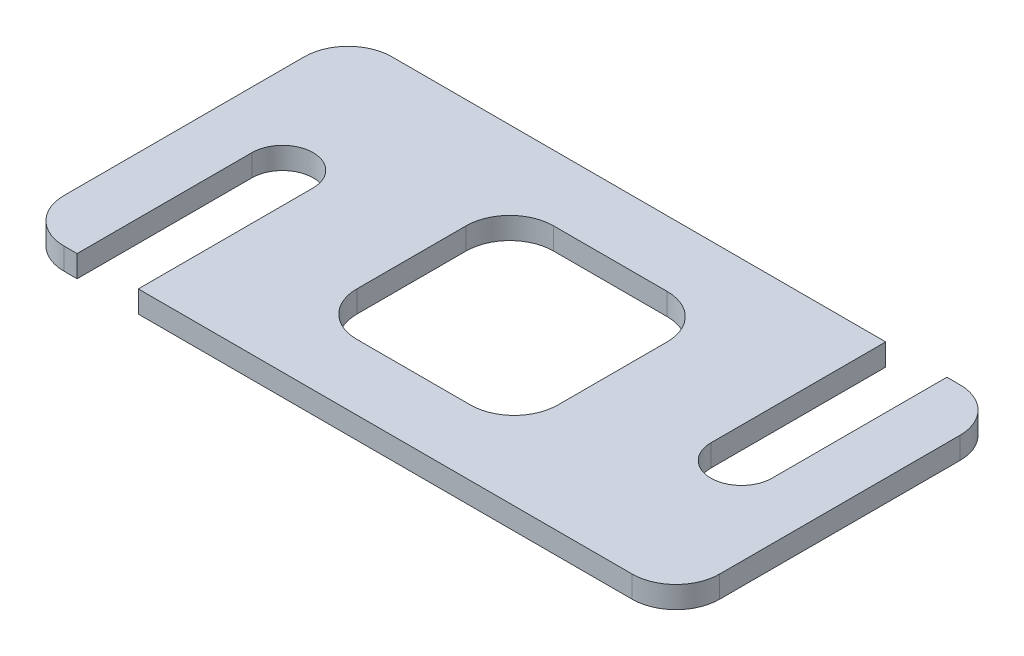
SolidWorks part; units mm, degrees
ref_plane "Front Plane" through (0, 0, 0) normal (0, 0, 1) x (1, 0, 0)
ref_plane "Top Plane" through (0, 0, 0) normal (0, 1, 0) x (1, 0, 0)
ref_plane "Right Plane" through (0, 0, 0) normal (1, 0, 0) x (0, 0, -1)
sketch "Sketch2" plane through (0, 0, 0) normal (0, 1, 0) x (1, 0, 0)
  line L0 (0, 0) -> (0, 75)
  line L1 (0, 75) -> (150, 75)
  line L2 (150, 75) -> (150, 0)
  line L3 (150, 0) -> (0, 0)
  dimension "D1" = 75
  dimension "D2" = 150
extrude "Boss-Extrude1" add sketch "Sketch2" along normal blind 5
sketch "Sketch3" plane through (0, 5, 0) normal (0, 1, 0) x (1, 0, 0)
  line L0 (13, 0) -> (13, 40)
  line L1 (0, 0) -> (150, 0) construction
  line L2 (27, 40) -> (27, 0)
  line L3 (27, 0) -> (13, 0)
  line L4 (137, 75) -> (137, 35)
  line L5 (150, 75) -> (0, 75) construction
  line L6 (123, 35) -> (123, 75)
  line L7 (123, 75) -> (137, 75)
  line L8 (0, 75) -> (0, 0) construction
  arc A0 (13, 40) -> (27, 40) centre (20, 40) cw
  arc A1 (137, 35) -> (123, 35) centre (130, 35) cw
  point P13 (20, 0)
  point P17 (17.1282, -1.4923)
  point P18 (130, 75)
  dimension "D4" = 7
  dimension "D1" = 7
  dimension "D2" = 40
  dimension "D3" = 20
  dimension "D5" = 20
  dimension "D6" = 40
extrude "Cut-Extrude1" cut sketch "Sketch3" against normal through all and the other way through all
sketch "Sketch4" plane through (0, 5, 0) normal (0, 1, 0) x (1, 0, 0)
  line L0 (52, 60) -> (98, 60)
  line L1 (98, 60) -> (98, 15)
  line L2 (98, 15) -> (52, 15)
  line L3 (52, 15) -> (52, 60)
  line L4 (123, 75) -> (0, 75) construction
  line L5 (27, 0) -> (150, 0) construction
  line L6 (123, 35) -> (123, 75) construction
  line L7 (27, 40) -> (27, 0) construction
  dimension "D1" = 15
  dimension "D2" = 15
  dimension "D3" = 25
  dimension "D4" = 25
extrude "Cut-Extrude2" cut sketch "Sketch4" against normal through all
fillet "Fillet1" radius 10 4 edges at (150, 2.5, 0) (150, 2.5, -75) (0, 2.5, 0) (0, 2.5, -75)
fillet "Fillet2" radius 10 4 edges at (98, 2.5, -15) (52, 2.5, -15) (98, 2.5, -60) (52, 2.5, -60)
